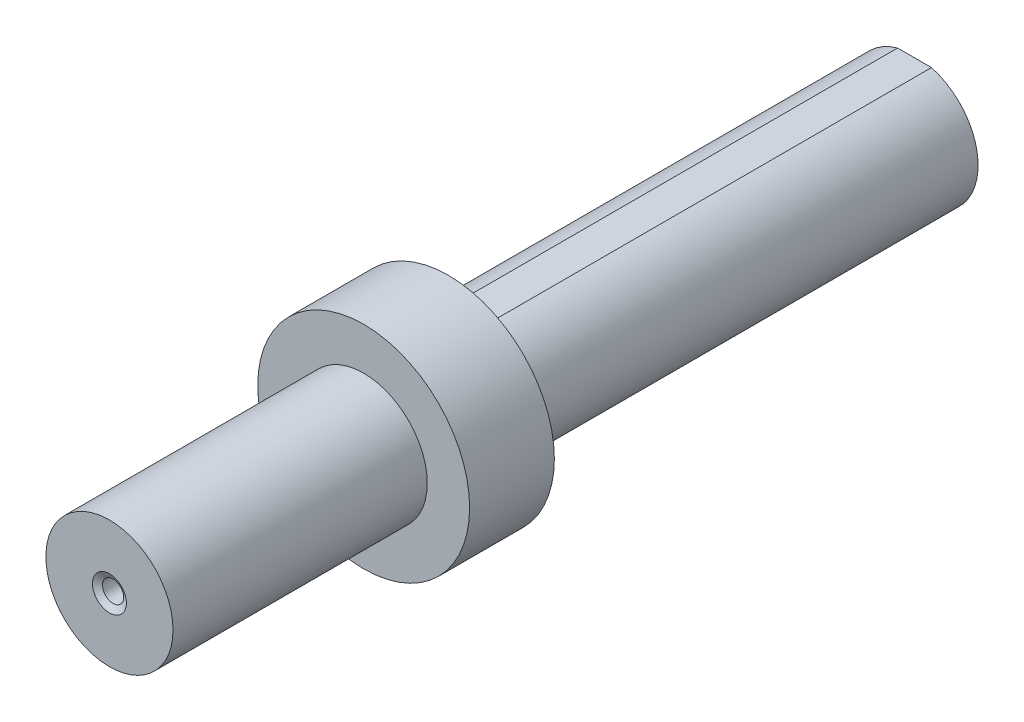
SolidWorks part; units mm, degrees
material "Chrome Stainless Steel"
ref_plane "Front Plane" through (0, 0, 0) normal (0, 0, 1) x (1, 0, 0)
ref_plane "Top Plane" through (0, 0, 0) normal (0, 1, 0) x (1, 0, 0)
ref_plane "Right Plane" through (0, 0, 0) normal (1, 0, 0) x (0, 0, -1)
sketch "Sketch1" plane through (0, 0, 0) normal (0, 0, 1) x (1, 0, 0)
  circle A0 centre (0, 0) radius 12.5
  dimension "D1" = 25
extrude "25mm dia" add sketch "Sketch1" along normal blind 10
sketch "Sketch2" plane through (0, 0, 10) normal (0, 0, 1) x (1, 0, 0)
  circle A0 centre (0, 0) radius 7.5
  dimension "D1" = 15
extrude "15mm dia bearing end" add sketch "Sketch2" along normal blind 40 from surface at -10 starting at face at (12.5, 0, 0)
sketch "Sketch3" plane through (0, 0, 0) normal (0, 0, -1) x (-1, 0, 0)
  circle A0 centre (0, 0) radius 7.5
  dimension "D1" = 15
extrude "15mm dia gear end" add sketch "Sketch3" along normal blind 55
hole_wizard "M3x0.5 Tapped Hole1" positions "Sketch6" profile "Sketch5" tap size "M3x0.5" standard "ANSI Metric"
sketch "Sketch6" plane through (0, 0, 40) normal (0, 0, 1) x (1, 0, 0)
  point P0 (0, 0)
sketch "Sketch5" plane through (0, 0, 40) normal (1, 0, 0) x (0, -1, 0)
  line L0 (0, 0) -> (0, 15.7511)
  line L1 (0, 15.7511) -> (1.25, 15)
  line L2 (1.25, 15) -> (1.25, 0.433)
  line L3 (1.25, 0.433) -> (2, 0)
  line L5 (2, 0) -> (0, 0)
  line L6 (-1.25, 0.433) -> (-2, 0) construction
  line L10 (0, 15.7511) -> (-1.25, 15) construction
  line L11 (0, -6.35) -> (0, 107.95) construction
  dimension "Tap Drill Dia." = 2.5
  dimension "Tap Drill Depth" = 15
  dimension "Near C'Sink Dia." = 4
  dimension "Near C'Sink Angle" = 120
  dimension "Drill Angle" = 118
cosmetic thread "Hole Thread1" parameters "D1"=12, "D2"=3
sketch "Sketch8" plane through (0, 0, -55) normal (0, 0, -1) x (-1, 0, 0)
  line L0 (0, -7.5) -> (0, 7.5) construction
  line L4 (-2, 7.2284) -> (2, 7.2284)
  line L5 (-2, 7.2284) -> (-2, 10.2538)
  line L6 (-2, 10.2538) -> (2, 10.2538)
  line L7 (2, 10.2538) -> (2, 7.2284)
  circle A0 centre (0, 0) radius 7.5 construction
  circle A4 centre (0, 0) radius 7.5 construction
  point P8 (0, 0)
  dimension "D1" = 4
extrude "Cut-Extrude1" cut sketch "Sketch8" against normal blind 55 contours L7 L4 L5 L6
equation "\"a\"= 1"
equation "\"b\"= 1"
equation "\"c\"= 1"
equation "\"d\"= 1"
equation "\"e\"= 1"
equation "\"x\"= 1"
equation "\"y\"= 1"
equation "\"z\"= 1"
